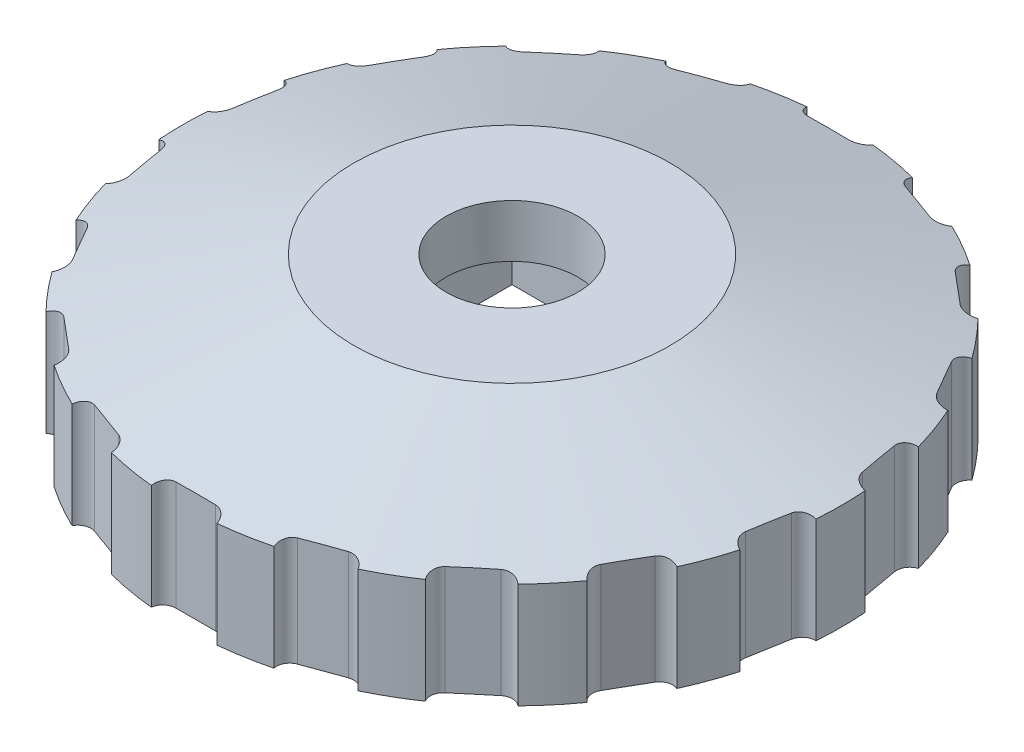
SolidWorks part; units mm, degrees
ref_plane "Front Plane" through (0, 0, 0) normal (0, 0, 1) x (1, 0, 0)
ref_plane "Top Plane" through (0, 0, 0) normal (0, 1, 0) x (1, 0, 0)
ref_plane "Right Plane" through (0, 0, 0) normal (1, 0, 0) x (0, 0, -1)
sketch "Sketch1" plane through (0, 0, 0) normal (0, 0, 1) x (1, 0, 0)
  line L0 (0, 6) -> (0, 0) construction
  line L1 (2.5, 0) -> (12.5, 0)
  line L2 (12.5, 0) -> (12.5, 4)
  line L3 (12.5, 4) -> (6, 6)
  line L4 (6, 6) -> (2.5, 6)
  line L5 (0, 6) -> (0, 0) construction
  line L6 (2.5, 6) -> (2.5, 0)
  line L7 (2.5, 6) -> (0, 6) construction
  line L8 (0, 0) -> (2.5, 0) construction
  dimension "D1" = 6
  dimension "D2" = 25
  dimension "D3" = 12
  dimension "D4" = 4
  dimension "D5" = 5
revolve "Revolve1" add sketch "Sketch1" angle 360 about L0
sketch "Sketch2" plane through (0, 0, 0) normal (0, -1, 0) x (1, 0, 0)
  line L0 (-0.75, 12.5) -> (0.75, 12.5) construction
  line L1 (-0.75, 13) -> (0.75, 13)
  line L2 (-0.75, 12) -> (0.75, 12)
  line L3 (0, 12.5) -> (0, 0) construction
  line L4 (3.5705, 12.0027) -> (4.98, 11.4896) construction
  line L5 (3.7415, 12.4725) -> (5.151, 11.9595)
  line L6 (3.3995, 11.5328) -> (4.809, 11.0198)
  line L7 (7.4603, 10.0576) -> (8.6094, 9.0935) construction
  line L8 (7.7817, 10.4407) -> (8.9308, 9.4765)
  line L9 (7.1389, 9.6746) -> (8.288, 8.7104)
  line L10 (10.4503, 6.8995) -> (11.2003, 5.6005) construction
  line L11 (10.8833, 7.1495) -> (11.6333, 5.8505)
  line L12 (10.0173, 6.6495) -> (10.7673, 5.3505)
  line L13 (12.1799, 2.9092) -> (12.4403, 1.432) construction
  line L14 (12.6723, 2.996) -> (12.9327, 1.5188)
  line L15 (11.6875, 2.8224) -> (11.9479, 1.3452)
  line L16 (12.4403, -1.432) -> (12.1799, -2.9092) construction
  line L17 (12.9327, -1.5188) -> (12.6723, -2.996)
  line L18 (11.9479, -1.3452) -> (11.6875, -2.8224)
  line L19 (11.2003, -5.6005) -> (10.4503, -6.8995) construction
  line L20 (11.6333, -5.8505) -> (10.8833, -7.1495)
  line L21 (10.7673, -5.3505) -> (10.0173, -6.6495)
  line L22 (8.6094, -9.0935) -> (7.4603, -10.0576) construction
  line L23 (8.9308, -9.4765) -> (7.7817, -10.4407)
  line L24 (8.288, -8.7104) -> (7.1389, -9.6746)
  line L25 (4.98, -11.4896) -> (3.5705, -12.0027) construction
  line L26 (5.151, -11.9595) -> (3.7415, -12.4725)
  line L27 (4.809, -11.0198) -> (3.3995, -11.5328)
  line L28 (0.75, -12.5) -> (-0.75, -12.5) construction
  line L29 (0.75, -13) -> (-0.75, -13)
  line L30 (0.75, -12) -> (-0.75, -12)
  line L31 (-3.5705, -12.0027) -> (-4.98, -11.4896) construction
  line L32 (-3.7415, -12.4725) -> (-5.151, -11.9595)
  line L33 (-3.3995, -11.5328) -> (-4.809, -11.0198)
  line L34 (-7.4603, -10.0576) -> (-8.6094, -9.0935) construction
  line L35 (-7.7817, -10.4407) -> (-8.9308, -9.4765)
  line L36 (-7.1389, -9.6746) -> (-8.288, -8.7104)
  line L37 (-10.4503, -6.8995) -> (-11.2003, -5.6005) construction
  line L38 (-10.8833, -7.1495) -> (-11.6333, -5.8505)
  line L39 (-10.0173, -6.6495) -> (-10.7673, -5.3505)
  line L40 (-12.1799, -2.9092) -> (-12.4403, -1.432) construction
  line L41 (-12.6723, -2.996) -> (-12.9327, -1.5188)
  line L42 (-11.6875, -2.8224) -> (-11.9479, -1.3452)
  line L43 (-12.4403, 1.432) -> (-12.1799, 2.9092) construction
  line L44 (-12.9327, 1.5188) -> (-12.6723, 2.996)
  line L45 (-11.9479, 1.3452) -> (-11.6875, 2.8224)
  line L46 (-11.2003, 5.6005) -> (-10.4503, 6.8995) construction
  line L47 (-11.6333, 5.8505) -> (-10.8833, 7.1495)
  line L48 (-10.7673, 5.3505) -> (-10.0173, 6.6495)
  line L49 (-8.6094, 9.0935) -> (-7.4603, 10.0576) construction
  line L50 (-8.9308, 9.4765) -> (-7.7817, 10.4407)
  line L51 (-8.288, 8.7104) -> (-7.1389, 9.6746)
  line L52 (-4.98, 11.4896) -> (-3.5705, 12.0027) construction
  line L53 (-5.151, 11.9595) -> (-3.7415, 12.4725)
  line L54 (-4.809, 11.0198) -> (-3.3995, 11.5328)
  circle A0 centre (0, 0) radius 12.5 construction
  arc A1 (-0.75, 13) -> (-0.75, 12) centre (-0.75, 12.5) ccw
  arc A2 (0.75, 12) -> (0.75, 13) centre (0.75, 12.5) ccw
  arc A3 (3.7415, 12.4725) -> (3.3995, 11.5328) centre (3.5705, 12.0027) ccw
  arc A4 (4.809, 11.0198) -> (5.151, 11.9595) centre (4.98, 11.4896) ccw
  arc A5 (7.7817, 10.4407) -> (7.1389, 9.6746) centre (7.4603, 10.0576) ccw
  arc A6 (8.288, 8.7104) -> (8.9308, 9.4765) centre (8.6094, 9.0935) ccw
  arc A7 (10.8833, 7.1495) -> (10.0173, 6.6495) centre (10.4503, 6.8995) ccw
  arc A8 (10.7673, 5.3505) -> (11.6333, 5.8505) centre (11.2003, 5.6005) ccw
  arc A9 (12.6723, 2.996) -> (11.6875, 2.8224) centre (12.1799, 2.9092) ccw
  arc A10 (11.9479, 1.3452) -> (12.9327, 1.5188) centre (12.4403, 1.432) ccw
  arc A11 (12.9327, -1.5188) -> (11.9479, -1.3452) centre (12.4403, -1.432) ccw
  arc A12 (11.6875, -2.8224) -> (12.6723, -2.996) centre (12.1799, -2.9092) ccw
  arc A13 (11.6333, -5.8505) -> (10.7673, -5.3505) centre (11.2003, -5.6005) ccw
  arc A14 (10.0173, -6.6495) -> (10.8833, -7.1495) centre (10.4503, -6.8995) ccw
  arc A15 (8.9308, -9.4765) -> (8.288, -8.7104) centre (8.6094, -9.0935) ccw
  arc A16 (7.1389, -9.6746) -> (7.7817, -10.4407) centre (7.4603, -10.0576) ccw
  arc A17 (5.151, -11.9595) -> (4.809, -11.0198) centre (4.98, -11.4896) ccw
  arc A18 (3.3995, -11.5328) -> (3.7415, -12.4725) centre (3.5705, -12.0027) ccw
  arc A19 (0.75, -13) -> (0.75, -12) centre (0.75, -12.5) ccw
  arc A20 (-0.75, -12) -> (-0.75, -13) centre (-0.75, -12.5) ccw
  arc A21 (-3.7415, -12.4725) -> (-3.3995, -11.5328) centre (-3.5705, -12.0027) ccw
  arc A22 (-4.809, -11.0198) -> (-5.151, -11.9595) centre (-4.98, -11.4896) ccw
  arc A23 (-7.7817, -10.4407) -> (-7.1389, -9.6746) centre (-7.4603, -10.0576) ccw
  arc A24 (-8.288, -8.7104) -> (-8.9308, -9.4765) centre (-8.6094, -9.0935) ccw
  arc A25 (-10.8833, -7.1495) -> (-10.0173, -6.6495) centre (-10.4503, -6.8995) ccw
  arc A26 (-10.7673, -5.3505) -> (-11.6333, -5.8505) centre (-11.2003, -5.6005) ccw
  arc A27 (-12.6723, -2.996) -> (-11.6875, -2.8224) centre (-12.1799, -2.9092) ccw
  arc A28 (-11.9479, -1.3452) -> (-12.9327, -1.5188) centre (-12.4403, -1.432) ccw
  arc A29 (-12.9327, 1.5188) -> (-11.9479, 1.3452) centre (-12.4403, 1.432) ccw
  arc A30 (-11.6875, 2.8224) -> (-12.6723, 2.996) centre (-12.1799, 2.9092) ccw
  arc A31 (-11.6333, 5.8505) -> (-10.7673, 5.3505) centre (-11.2003, 5.6005) ccw
  arc A32 (-10.0173, 6.6495) -> (-10.8833, 7.1495) centre (-10.4503, 6.8995) ccw
  arc A33 (-8.9308, 9.4765) -> (-8.288, 8.7104) centre (-8.6094, 9.0935) ccw
  arc A34 (-7.1389, 9.6746) -> (-7.7817, 10.4407) centre (-7.4603, 10.0576) ccw
  arc A35 (-5.151, 11.9595) -> (-4.809, 11.0198) centre (-4.98, 11.4896) ccw
  arc A36 (-3.3995, 11.5328) -> (-3.7415, 12.4725) centre (-3.5705, 12.0027) ccw
  point P4 (0, 12.5)
  point P13 (4.2753, 11.7462)
  point P23 (8.0348, 9.5756)
  point P30 (10.8253, 6.25)
  point P37 (12.3101, 2.1706)
  point P44 (12.3101, -2.1706)
  point P51 (10.8253, -6.25)
  point P58 (8.0348, -9.5756)
  point P65 (4.2753, -11.7462)
  point P72 (0, -12.5)
  point P79 (-4.2753, -11.7462)
  point P86 (-8.0348, -9.5756)
  point P93 (-10.8253, -6.25)
  point P100 (-12.3101, -2.1706)
  point P107 (-12.3101, 2.1706)
  point P114 (-10.8253, 6.25)
  point P121 (-8.0348, 9.5756)
  point P128 (-4.2753, 11.7462)
  point P133 (0, 0)
  dimension "D2" = 0.5
  dimension "D1" = 1.5
  dimension "D3" = 18
extrude "Cut-Extrude1" cut sketch "Sketch2" against normal blind 10 contours L2 A2 L1 A1
sketch "Sketch4" plane through (0, 0, 0) normal (0, 1, 0) x (1, 0, 0)
  line L1 (-5, -5) -> (5, -5)
  line L2 (-5, -5) -> (-5, 5)
  line L3 (-5, 5) -> (5, 5)
  line L4 (5, -5) -> (5, 5)
  line L5 (-5, -5) -> (5, 5) construction
  line L6 (-5, 5) -> (5, -5) construction
  point P0 (0, 0)
  dimension "D1" = 10
extrude "Cut-Extrude2" cut sketch "Sketch4" along normal blind 4
